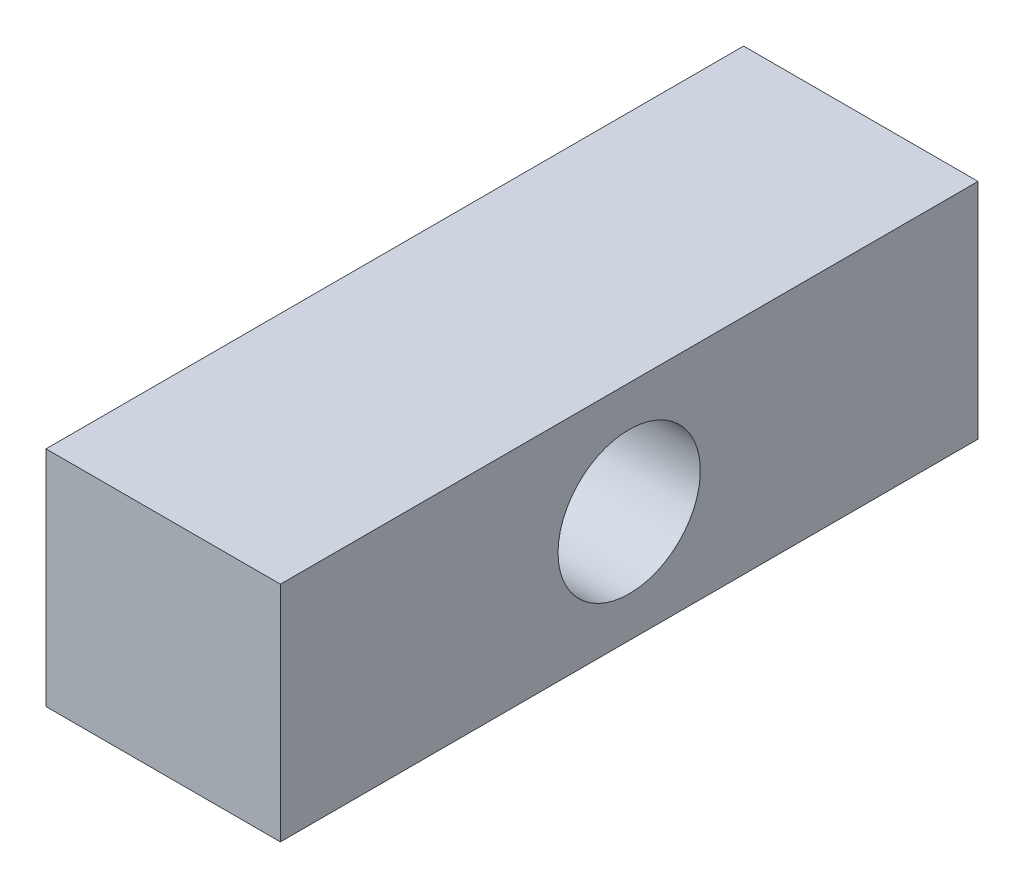
SolidWorks part; units mm, degrees
ref_plane "前视基准面" through (0, 0, 0) normal (0, 0, 1) x (1, 0, 0)
ref_plane "上视基准面" through (0, 0, 0) normal (0, 1, 0) x (1, 0, 0)
ref_plane "右视基准面" through (0, 0, 0) normal (1, 0, 0) x (0, 0, -1)
sketch "草图1" plane through (0, 0, 0) normal (1, 0, 0) x (0, 0, -1)
  line L1 (-250, -80) -> (250, -80)
  line L2 (-250, -80) -> (-250, 80)
  line L3 (-250, 80) -> (250, 80)
  line L4 (250, -80) -> (250, 80)
  line L5 (-250, -80) -> (250, 80) construction
  line L6 (-250, 80) -> (250, -80) construction
  circle A0 centre (0, 0) radius 51
extrude "凸台-拉伸1" add sketch "草图1" along normal blind 168
